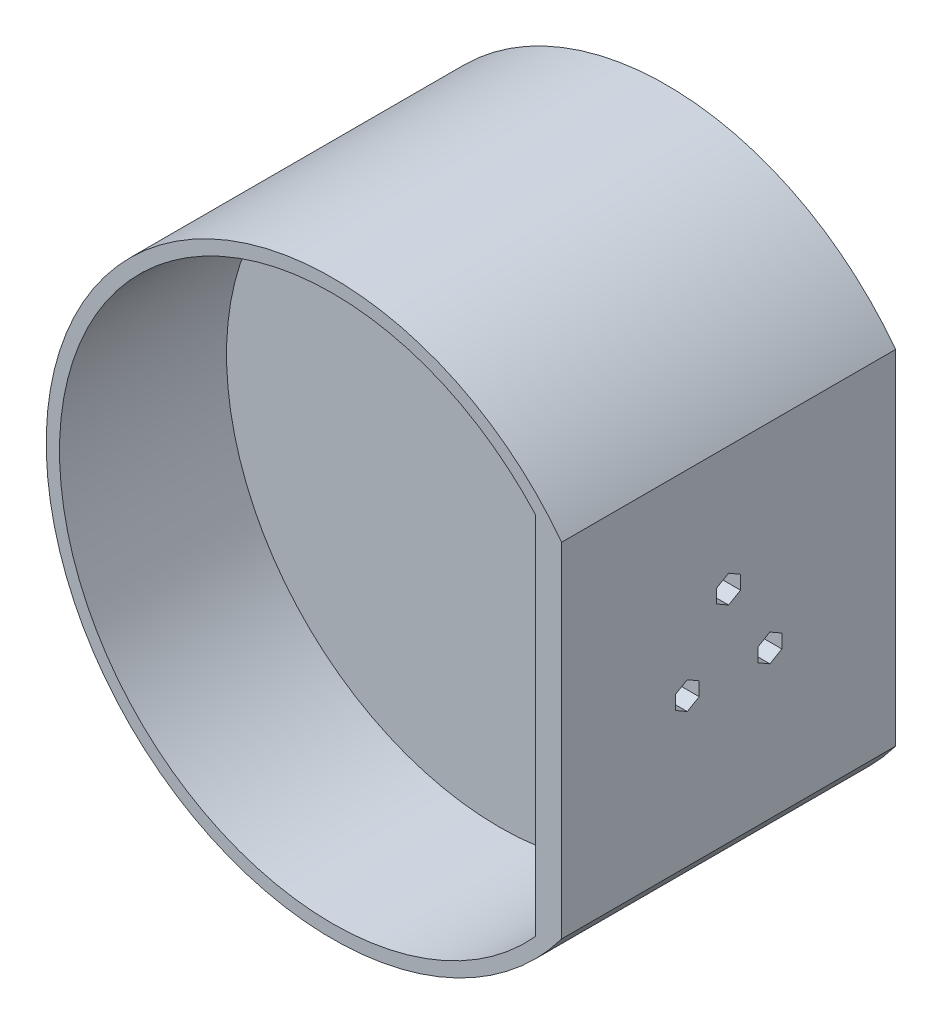
SolidWorks part; units mm, degrees
ref_plane "前视基准面" through (0, 0, 0) normal (0, 0, 1) x (1, 0, 0)
ref_plane "上视基准面" through (0, 0, 0) normal (0, 1, 0) x (1, 0, 0)
ref_plane "右视基准面" through (0, 0, 0) normal (1, 0, 0) x (0, 0, -1)
other "Configuration Table"
sketch "草图1" plane through (0, 0, 0) normal (0, 0, 1) x (1, 0, 0)
  line L0 (48, 36) -> (48, -36)
  arc A0 (48, 36) -> (48, -36) centre (0, 0) ccw
  dimension "D1" = 60
extrude "凸台-拉伸3" add sketch "草图1" along normal blind 70
sketch "草图4" plane through (48, 0, 0) normal (1, 0, 0) x (0, 0, -1)
  line L0 (-28.8397, -3.5566) -> (-28.8397, -6.4434)
  line L1 (-35, 7.1132) -> (-32.5, 8.5566)
  line L2 (-32.5, 8.5566) -> (-32.5, 11.4434)
  line L3 (-32.5, 11.4434) -> (-35, 12.8868)
  line L4 (-35, 12.8868) -> (-37.5, 11.4434)
  line L5 (-37.5, 11.4434) -> (-37.5, 8.5566)
  line L6 (-37.5, 8.5566) -> (-35, 7.1132)
  line L7 (-28.8397, -6.4434) -> (-26.3397, -7.8868)
  line L8 (-26.3397, -7.8868) -> (-23.8397, -6.4434)
  line L9 (-23.8397, -6.4434) -> (-23.8397, -3.5566)
  line L10 (-23.8397, -3.5566) -> (-26.3397, -2.1132)
  line L11 (-26.3397, -2.1132) -> (-28.8397, -3.5566)
  line L12 (-41.1603, -3.5566) -> (-43.6603, -2.1132)
  line L13 (-43.6603, -2.1132) -> (-46.1603, -3.5566)
  line L14 (-46.1603, -3.5566) -> (-46.1603, -6.4434)
  line L15 (-46.1603, -6.4434) -> (-43.6603, -7.8868)
  line L16 (-43.6603, -7.8868) -> (-41.1603, -6.4434)
  line L17 (-41.1603, -6.4434) -> (-41.1603, -3.5566)
  circle A0 centre (-35, 10) radius 2.5 construction
  point P0 (-35, 0)
  point P24 (-35, 0)
  dimension "D1" = 5
  dimension "D2" = 10
  dimension "D3" = 3
extrude "切除-拉伸2" cut sketch "草图4" against normal blind 5
sketch "草图6" plane through (0, 0, 70) normal (0, 0, 1) x (1, 0, 0)
  line L2 (42.4985, 38.3064) -> (42.4985, -38.3064)
  arc A0 (42.4985, 38.3064) -> (42.4985, -38.3064) centre (0, 0) ccw
extrude "切除-拉伸4" cut sketch "草图6" against normal blind 35
